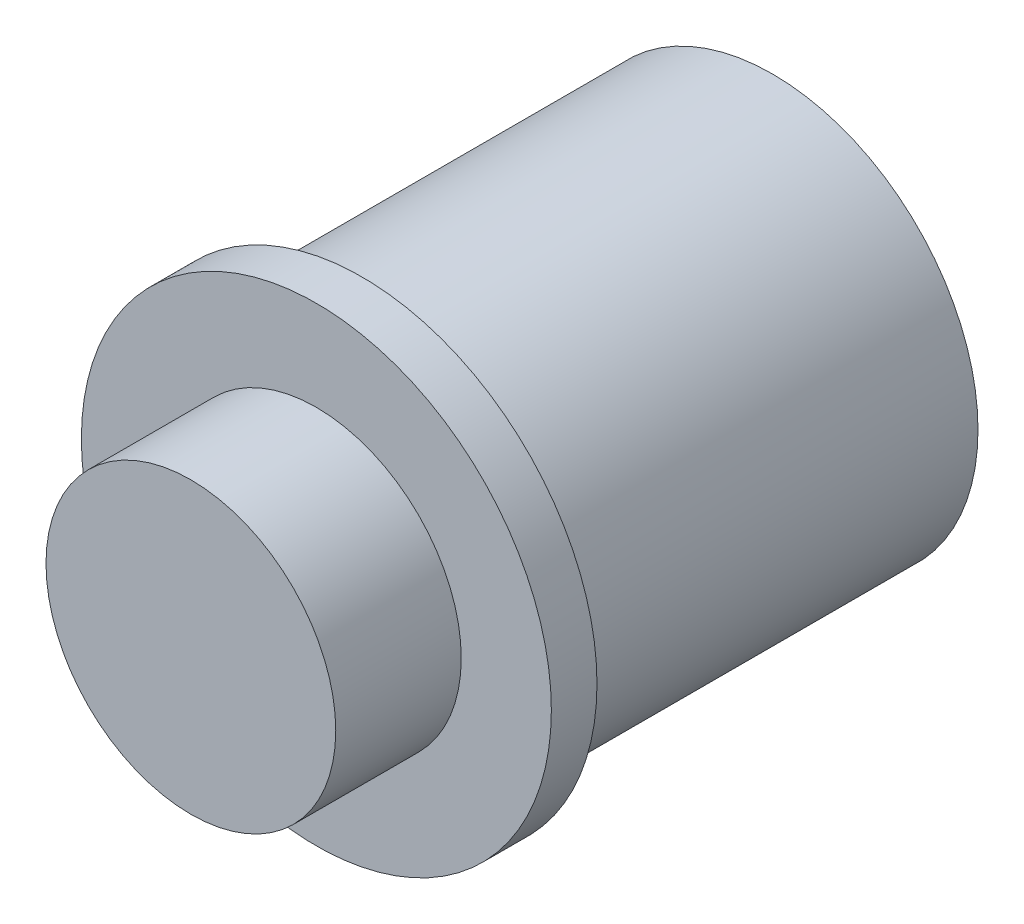
SolidWorks part; units mm, degrees
ref_plane "Front Plane" through (0, 0, 0) normal (0, 0, 1) x (1, 0, 0)
ref_plane "Top Plane" through (0, 0, 0) normal (0, 1, 0) x (1, 0, 0)
ref_plane "Right Plane" through (0, 0, 0) normal (1, 0, 0) x (0, 0, -1)
sketch "Sketch1" plane through (0, 0, 0) normal (0, 0, 1) x (1, 0, 0)
  circle A0 centre (0, 0) radius 9
  dimension "D1" = 18
extrude "Boss-Extrude1" add sketch "Sketch1" along normal blind 18
sketch "Sketch2" plane through (0, 0, 18) normal (0, 0, 1) x (1, 0, 0)
  circle A0 centre (0, 0) radius 10.3
  dimension "D1" = 20.6
extrude "Boss-Extrude2" add sketch "Sketch2" along normal blind 2
sketch "Sketch3" plane through (0, 0, 20) normal (0, 0, 1) x (1, 0, 0)
  circle A0 centre (0, 0) radius 6.35
  dimension "D1" = 12.7
extrude "Boss-Extrude3" add sketch "Sketch3" along normal blind 5.5
